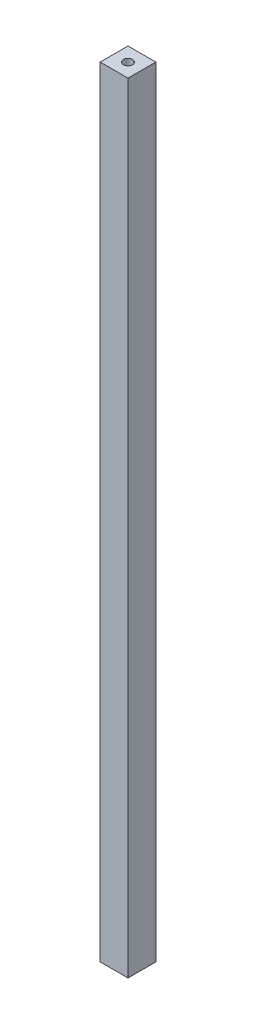
SolidWorks part; units mm, degrees
ref_plane "Front Plane" through (0, 0, 0) normal (0, 0, 1) x (1, 0, 0)
ref_plane "Top Plane" through (0, 0, 0) normal (0, 1, 0) x (1, 0, 0)
ref_plane "Right Plane" through (0, 0, 0) normal (1, 0, 0) x (0, 0, -1)
sketch "Sketch1" plane through (0, 0, 0) normal (0, 1, 0) x (1, 0, 0)
  line L1 (7.5, -7.5) -> (-7.5, -7.5)
  line L2 (7.5, -7.5) -> (7.5, 7.5)
  line L3 (7.5, 7.5) -> (-7.5, 7.5)
  line L4 (-7.5, -7.5) -> (-7.5, 7.5)
  line L5 (7.5, -7.5) -> (-7.5, 7.5) construction
  line L6 (7.5, 7.5) -> (-7.5, -7.5) construction
  circle A0 centre (0, 0) radius 2.5
  point P0 (0, 0)
  dimension "D1" = 15
  dimension "D2" = 15
extrude "Boss-Extrude1" add sketch "Sketch1" along normal blind 420
